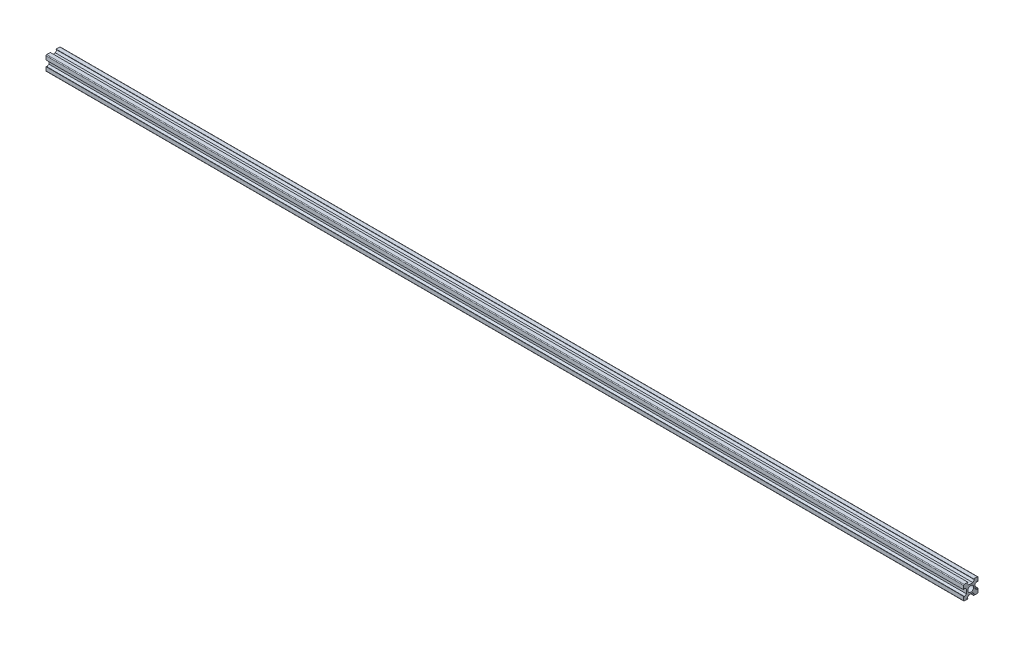
SolidWorks part; units mm, degrees
ref_plane "前视基准面" through (0, 0, 0) normal (0, 0, 1) x (1, 0, 0)
ref_plane "上视基准面" through (0, 0, 0) normal (0, 1, 0) x (1, 0, 0)
ref_plane "右视基准面" through (0, 0, 0) normal (1, 0, 0) x (0, 0, -1)
sketch "草图1" plane through (0, 0, 0) normal (0, 0, 1) x (1, 0, 0)
  line L1 (-66.5187, -1.3979) -> (1203.4813, -1.3979)
  line L2 (-66.5187, -1.3979) -> (-66.5187, -11.3979)
  line L3 (-66.5187, -11.3979) -> (1203.4813, -11.3979)
  line L4 (1203.4813, -1.3979) -> (1203.4813, -11.3979)
  dimension "D1" = 10
  dimension "D2" = 1270
extrude "凸台-拉伸1" add sketch "草图1" along normal blind 10
sketch "草图2" plane through (1203.4813, 0, 0) normal (1, 0, 0) x (0, 0, -1)
  circle A0 centre (0, -11.3979) radius 4
  dimension "D1" = 8
extrude "切除-拉伸1" cut sketch "草图2" against normal blind 1270
sketch "草图3" plane through (1203.4813, 0, 0) normal (1, 0, 0) x (0, 0, -1)
  line L0 (-4, -1.3979) -> (0, -1.3979)
  line L1 (-10, -11.3979) -> (-10, -1.3979) construction
  line L2 (-10, -1.3979) -> (0, -1.3979) construction
  line L3 (-10, -7.3979) -> (-10, -11.3979)
  line L4 (-4, -1.3979) -> (-4, -1.8979)
  line L5 (-4, -1.8979) -> (-5.5, -1.8979)
  line L6 (-3, -5.3979) -> (0, -5.3979)
  line L7 (0, -7.3979) -> (0, -1.3979) construction
  line L8 (0, -5.3979) -> (0, -1.3979)
  line L9 (-10, -11.3979) -> (-6, -11.3979)
  line L10 (-10, -11.3979) -> (-4, -11.3979) construction
  line L11 (-6, -11.3979) -> (-6, -8.3979)
  line L12 (-10, -7.3979) -> (-9.5, -7.3979)
  line L13 (-9.5, -7.3979) -> (-9.5, -5.8979)
  line L14 (-5.5, -1.8979) -> (-3, -5.3979)
  line L15 (-9.5, -5.8979) -> (-6, -8.3979)
  dimension "D1" = 4
  dimension "D2" = 4
  dimension "D3" = 4
  dimension "D4" = 4
  dimension "D5" = 0.5
  dimension "D6" = 0.5
  dimension "D7" = 3
  dimension "D8" = 3
  dimension "D9" = 1.5
  dimension "D10" = 1.5
extrude "切除-拉伸2" cut sketch "草图3" against normal blind 1270
fillet "圆角1" radius 1 1 edges at (568.4813, -1.3979, 10)
pattern_circular "阵列(圆周)2" count 4 every 90 about axis through (0, -11.3979, 0) along (1, 0, 0) of "凸台-拉伸1", "圆角1", "切除-拉伸1", "切除-拉伸2"
